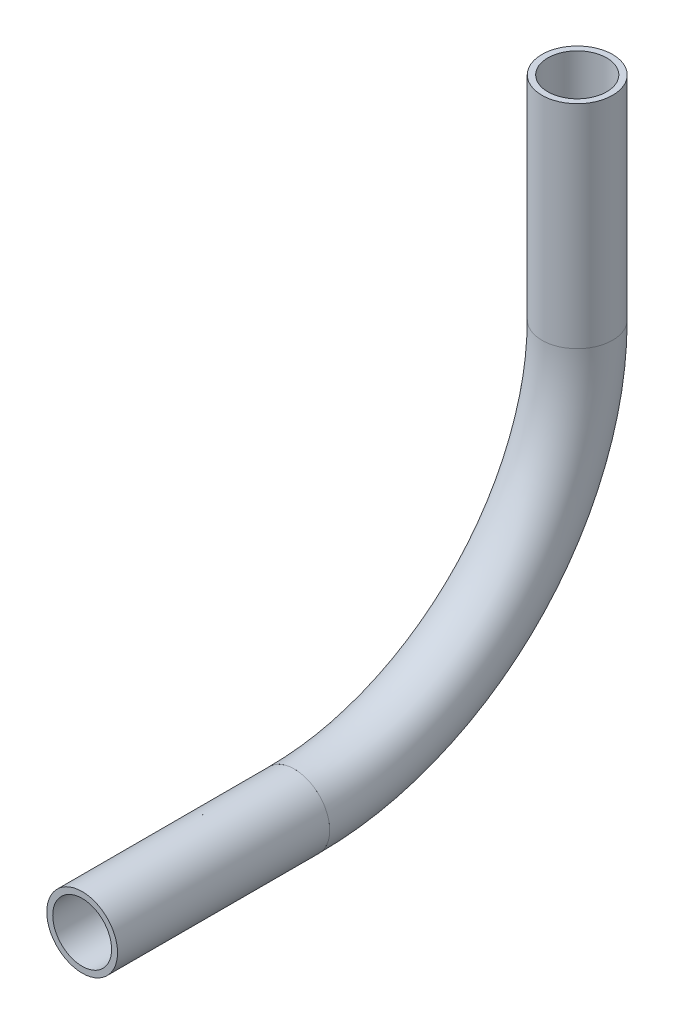
SolidWorks part; units mm, degrees
ref_plane "Front Plane" through (0, 0, 0) normal (0, 0, 1) x (1, 0, 0)
ref_plane "Top Plane" through (0, 0, 0) normal (0, 1, 0) x (1, 0, 0)
ref_plane "Right Plane" through (0, 0, 0) normal (1, 0, 0) x (0, 0, -1)
sketch "Sketch3" plane through (0, 0, 0) normal (1, 0, 0) x (0, 0, -1)
  line L0 (-259.1796, -187.8489) -> (-259.1796, -225.9489)
  line L1 (-309.9796, -276.7489) -> (-348.0796, -276.7489)
  arc A0 (-259.1796, -225.9489) -> (-309.9796, -276.7489) centre (-309.9796, -225.9489) cw
  dimension "D1" = 50.8
  dimension "D2" = 38.1
  dimension "D3" = 38.1
other "Pipe 0.5 SCH 40(1)"
ref_plane "Plane1" through (0, -187.8489, 259.1796) normal (0, -1, 0) x (0, 0, -1)
sketch "Sketch1" plane through (0, -187.8489, 259.1796) normal (0, -1, 0) x (0, 0, -1)
  circle A0 centre (0, 0) radius 6.35
  circle A1 centre (0, 0) radius 5.2832
  point P5 (0, 0)
  dimension "In_dia" = 12.7
  dimension "Out_dia" = 10.5664
